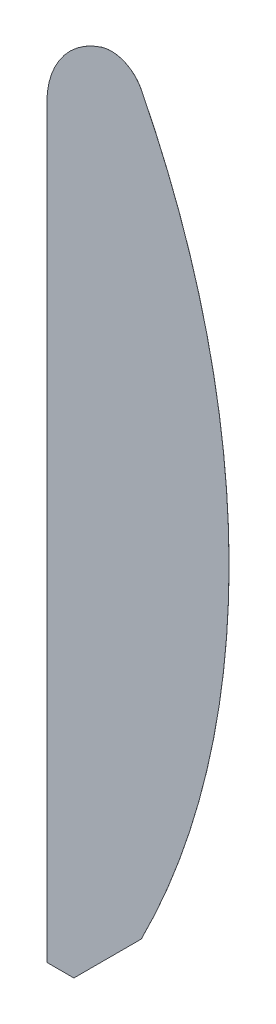
SolidWorks part; units mm, degrees
ref_plane "Front Plane" through (0, 0, 0) normal (1, 0, 0) x (0, 1, 0)
ref_plane "Top Plane" through (0, 0, 0) normal (0, 0, 1) x (0, 1, 0)
ref_plane "Right Plane" through (0, 0, 0) normal (0, 1, 0) x (-1, 0, 0)
sketch "Sketch1" plane through (0, 0, 0) normal (0, 0, 1) x (0, 1, 0)
  line L0 (0, 0) -> (0, 46433.2994) construction
  line L1 (0, 0) -> (-46433.2994, 0) construction
  line L2 (341.0561, 447.2498) -> (1519.4065, 281.6435) construction
  line L3 (0, 0) -> (138.168, 0)
  line L9 (0, 0) -> (0, -5)
  line L10 (0, -5) -> (12.5, -17.5)
  line L11 (0, 0) -> (80.7012, -33.7778)
  arc A0 (138.168, 0) -> (152, -10) centre (138.168, -14.5662) cw
  arc A1 (152, -10) -> (148.9023, -17.5) centre (146.093, -11.95) cw
  arc A2 (12.5, -17.5) -> (148.9023, -17.5) centre (80.7012, 117.2369) ccw
  dimension "D1" = 138.168
  dimension "D2" = 5
  dimension "D3" = 33.7778
  dimension "D4" = 17.5
  dimension "Span" = 152
  dimension "D6" = 12.5
  dimension "D7" = 10
extrude "Boss-Extrude1" add sketch "Sketch1" along normal blind 0.01 contours L3 A0 A1 A2 L10 L9
equation "\"D3@Sketch1\"=\"Span@Sketch1\"/4.5"
equation "\"D1@Sketch1\"=\"Span@Sketch1\"*0.909"
